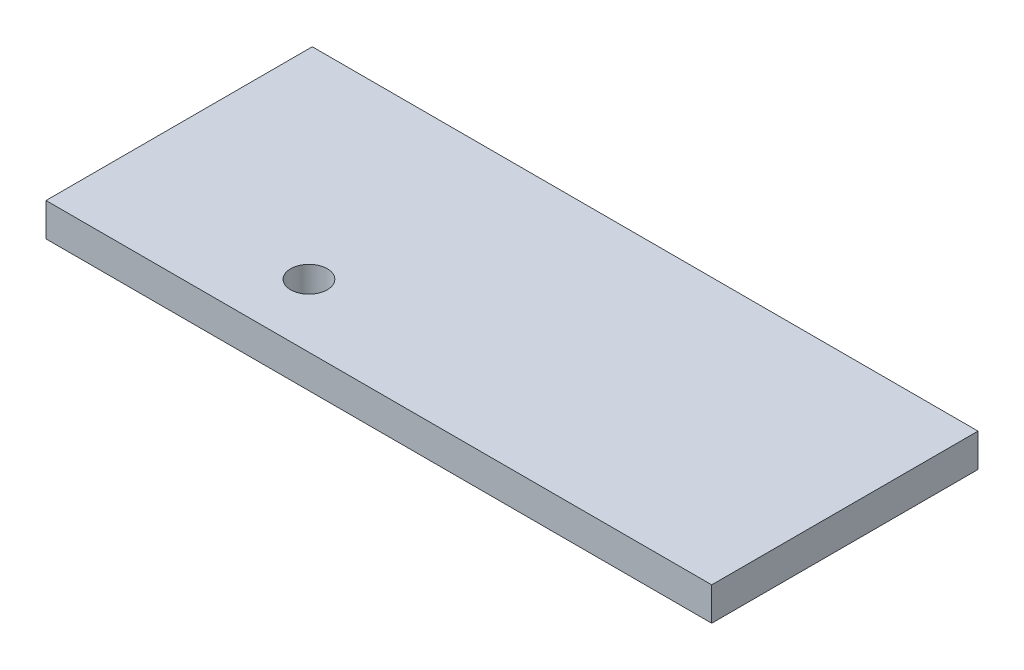
SolidWorks part; units mm, degrees
ref_plane "정면" through (0, 0, 0) normal (0, 0, 1) x (1, 0, 0)
ref_plane "윗면" through (0, 0, 0) normal (0, 1, 0) x (1, 0, 0)
ref_plane "우측면" through (0, 0, 0) normal (1, 0, 0) x (0, 0, -1)
sketch "스케치1" plane through (0, 0, 0) normal (0, 1, 0) x (1, 0, 0)
  line L1 (0, 0) -> (400, 0)
  line L2 (0, 0) -> (0, 160)
  line L3 (0, 160) -> (400, 160)
  line L4 (400, 0) -> (400, 160)
  circle A0 centre (120, 38) radius 11
  dimension "D3" = 22
  dimension "D1" = 400
  dimension "D2" = 160
  dimension "D4" = 38
  dimension "D5" = 120
extrude "보스-돌출1" add sketch "스케치1" along normal blind 20
